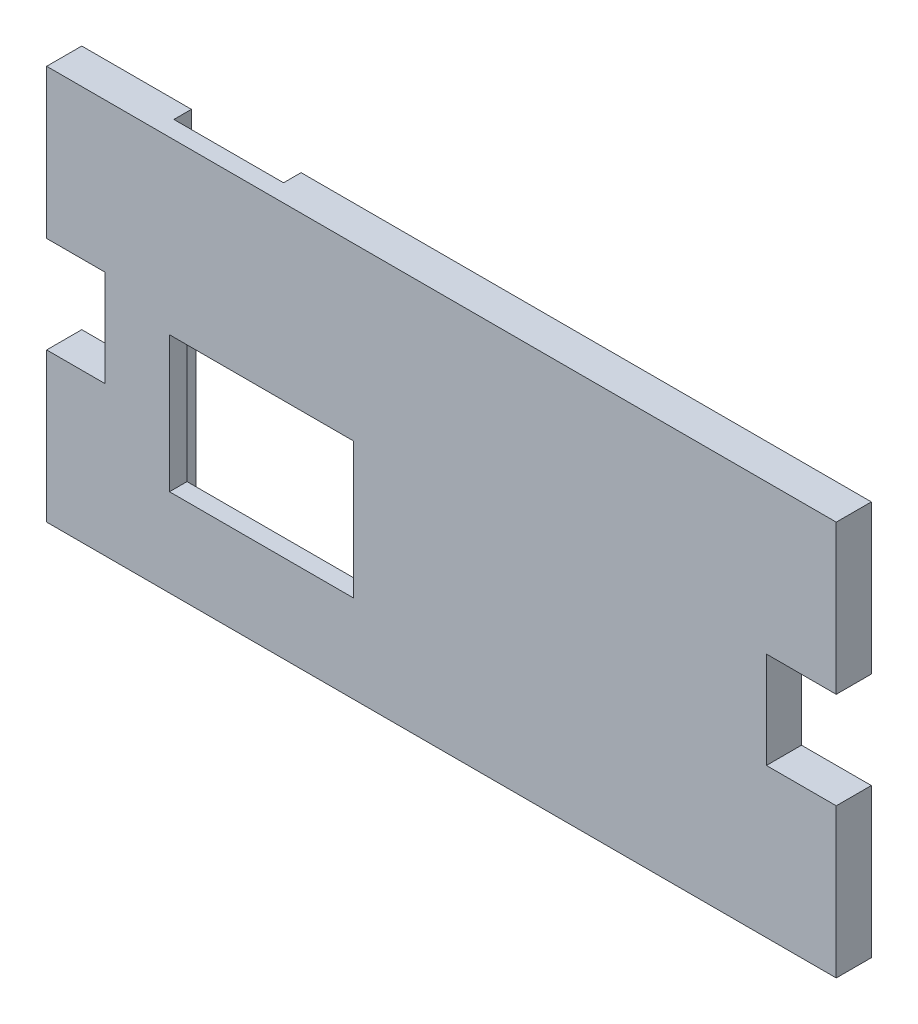
SolidWorks part; units mm, degrees
ref_plane "Front Plane" through (0, 0, 0) normal (0, 0, 1) x (1, 0, 0)
ref_plane "Top Plane" through (0, 0, 0) normal (0, 1, 0) x (1, 0, 0)
ref_plane "Right Plane" through (0, 0, 0) normal (1, 0, 0) x (0, 0, -1)
sketch "Sketch1" plane through (0, 0, 0) normal (0, 0, 1) x (1, 0, 0)
  line L1 (-90, 45) -> (90, 45)
  line L2 (-90, 45) -> (-90, -45)
  line L3 (-90, -45) -> (90, -45)
  line L4 (90, 45) -> (90, -45)
  line L5 (-90, 45) -> (90, -45) construction
  line L6 (-90, -45) -> (90, 45) construction
  point P0 (0, 0)
  dimension "D1" = 180
  dimension "D2" = 90
extrude "Boss-Extrude1" add sketch "Sketch1" along normal blind 8
sketch "Sketch3" plane through (0, 0, 0) normal (0, 0, -1) x (-1, 0, 0)
  line L0 (-90, -45) -> (-90, 45) construction
  line L1 (-85, -30) -> (-75, -30)
  line L2 (-85, -30) -> (-85, -40)
  line L3 (-85, -40) -> (-75, -40)
  line L4 (-75, -30) -> (-75, -40)
  line L5 (-85, -30) -> (-75, -40) construction
  line L6 (-85, -40) -> (-75, -30) construction
  line L7 (-85, 40) -> (-75, 40)
  line L8 (-85, 40) -> (-85, 30)
  line L9 (-85, 30) -> (-75, 30)
  line L10 (-75, 40) -> (-75, 30)
  line L11 (-85, 40) -> (-75, 30) construction
  line L12 (-85, 30) -> (-75, 40) construction
  line L13 (75, 40) -> (85, 40)
  line L14 (75, 40) -> (75, 30)
  line L15 (75, 30) -> (85, 30)
  line L16 (85, 40) -> (85, 30)
  line L17 (75, 40) -> (85, 30) construction
  line L18 (75, 30) -> (85, 40) construction
  line L19 (75, -30) -> (85, -30)
  line L20 (75, -30) -> (75, -40)
  line L21 (75, -40) -> (85, -40)
  line L22 (85, -30) -> (85, -40)
  line L23 (75, -30) -> (85, -40) construction
  line L24 (75, -40) -> (85, -30) construction
  line L25 (90, 45) -> (90, -45) construction
  line L26 (90, -45) -> (-90, -45) construction
  line L27 (-90, 45) -> (90, 45) construction
  point P0 (-80, -35)
  point P5 (-80, 35)
  point P10 (80, 35)
  point P15 (80, -35)
  point P28 (-85, -35)
  point P29 (80, -40)
  point P30 (-75, 35)
  point P31 (75, 35)
  point P32 (85, 35)
  point P33 (0, 0)
  point P34 (75, -35)
  dimension "D1" = 5
  dimension "D2" = 5
  dimension "D3" = 5
  dimension "D4" = 5
  dimension "D5" = 5
  dimension "D6" = 5
  dimension "D7" = 5
  dimension "D8" = 5
  dimension "D9" = 10
  dimension "D10" = 10
  dimension "D11" = 10
  dimension "D12" = 10
  dimension "D13" = 10
  dimension "D14" = 10
  dimension "D15" = 10
  dimension "D16" = 10
extrude "Cut-Extrude1" cut sketch "Sketch3" against normal blind 7
sketch "Sketch4" plane through (0, 0, 0) normal (0, 0, -1) x (-1, 0, 0)
  line L0 (-90, 45) -> (90, 45) construction
  line L1 (40, 45) -> (65, 45)
  line L2 (40, 45) -> (40, 15)
  line L3 (40, 15) -> (65, 15)
  line L4 (65, 45) -> (65, 15)
  line L5 (40, 45) -> (65, 15) construction
  line L6 (40, 15) -> (65, 45) construction
  line L7 (-50, 40) -> (-5, 40)
  line L8 (-50, 40) -> (-50, -40)
  line L9 (-50, -40) -> (-5, -40)
  line L10 (-5, 40) -> (-5, -40)
  line L11 (18, 11) -> (64, 11)
  line L12 (18, 11) -> (18, -35)
  line L13 (18, -35) -> (64, -35)
  line L14 (64, 11) -> (64, -35)
  line L15 (75, 40) -> (75, 30) construction
  line L16 (75, -30) -> (75, -40) construction
  line L17 (90, -45) -> (-90, -45) construction
  line L18 (-75, -40) -> (-75, -30) construction
  point P0 (52.5, 30)
  point P17 (75, 35)
  dimension "D1" = 0
  dimension "D2" = 25
  dimension "D3" = 30
  dimension "D4" = 10
  dimension "D5" = 11
  dimension "D6" = 46
  dimension "D7" = 46
  dimension "D8" = 10
  dimension "D9" = 25
  dimension "D10" = 5
  dimension "D11" = 5
  dimension "D12" = 45
extrude "Cut-Extrude2" cut sketch "Sketch4" against normal blind 4
sketch "Sketch5" plane through (0, 0, 0) normal (0, 0, -1) x (-1, 0, 0)
  line L0 (-90, -45) -> (-90, 45) construction
  line L1 (-90, 11) -> (-74.0824, 11)
  line L2 (-90, 11) -> (-90, -11)
  line L3 (-90, -11) -> (-74.0824, -11)
  line L4 (-74.0824, 11) -> (-74.0824, -11)
  line L5 (90, 11) -> (76.7353, 11)
  line L6 (90, 11) -> (90, -11)
  line L7 (90, -11) -> (76.7353, -11)
  line L8 (76.7353, 11) -> (76.7353, -11)
  line L9 (90, 45) -> (90, -45) construction
  line L10 (-90, 45) -> (40, 45) construction
  line L11 (90, -45) -> (-90, -45) construction
  line L12 (65, 45) -> (90, 45) construction
  point P10 (-90, 0)
  point P19 (83.3677, 11)
  dimension "D1" = 0
  dimension "D2" = 0
  dimension "D3" = 34
  dimension "D4" = 34
  dimension "D5" = 34
  dimension "D6" = 34
extrude "Cut-Extrude3" cut sketch "Sketch5" against normal through all
sketch "Sketch6" plane through (0, 0, 0) normal (0, 0, -1) x (-1, 0, 0)
  line L0 (18, -35) -> (64, -35) construction
  line L1 (20, 6) -> (62, 6)
  line L2 (20, 6) -> (20, -25)
  line L3 (20, -25) -> (62, -25)
  line L4 (62, 6) -> (62, -25)
  line L5 (64, 11) -> (18, 11) construction
  line L6 (64, -35) -> (64, 11) construction
  line L7 (18, 11) -> (18, -35) construction
  point P12 (18, -12)
  dimension "D1" = 10
  dimension "D2" = 5
  dimension "D3" = 2
  dimension "D4" = 2
extrude "Cut-Extrude12" cut sketch "Sketch6" against normal through all and the other way through all
